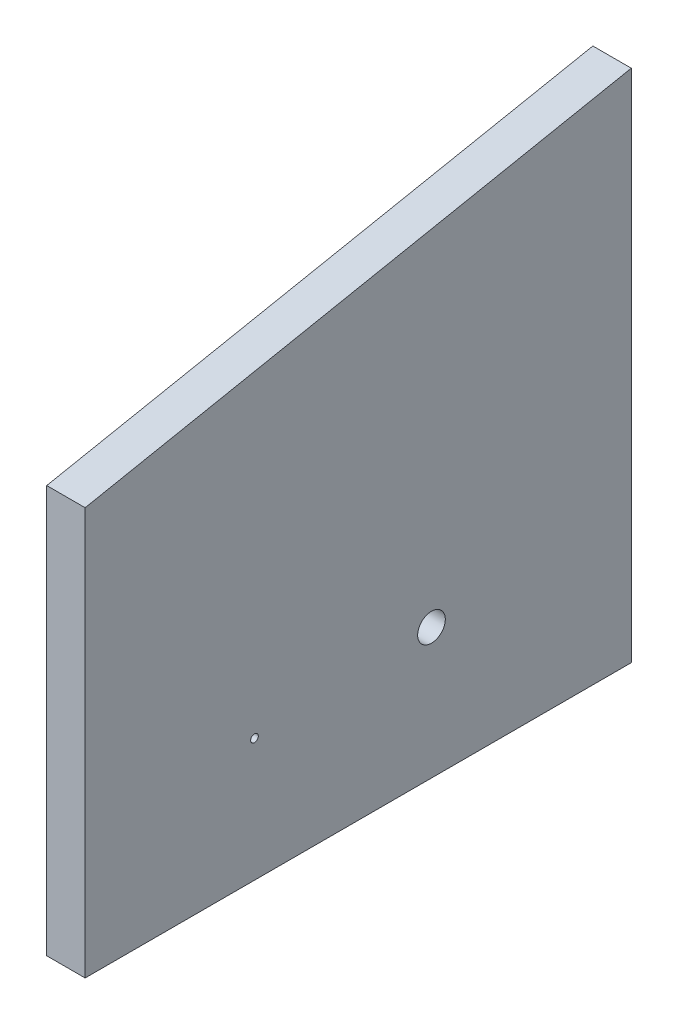
SolidWorks part; units mm, degrees
ref_plane "前视基准面" through (0, 0, 0) normal (0, 0, 1) x (1, 0, 0)
ref_plane "上视基准面" through (0, 0, 0) normal (0, 1, 0) x (1, 0, 0)
ref_plane "右视基准面" through (0, 0, 0) normal (1, 0, 0) x (0, 0, -1)
sketch "Sketch1" plane through (0, 0, 0) normal (0, 1, 0) x (1, 0, 0)
  line L1 (0, 0) -> (50, 0)
  line L2 (0, 0) -> (0, 9.1)
  line L3 (0, 9.1) -> (50, 9.1)
  line L4 (50, 0) -> (50, 9.1)
  dimension "D1" = 50
  dimension "D2" = 9.1
extrude "Boss-Extrude1" add sketch "Sketch1" along normal blind 2
sketch "Sketch2" plane through (0, 2, 0) normal (0, 1, 0) x (1, 0, 0)
  line L0 (50, 9.1) -> (0, 9.1) construction
  line L1 (12.5, 9.1) -> (37.5, 9.1)
  line L2 (12.5, 9.1) -> (12.5, 2.5)
  line L3 (12.5, 2.5) -> (37.5, 2.5)
  line L4 (37.5, 9.1) -> (37.5, 2.5)
  line L5 (0, 9.1) -> (0, 0) construction
  line L6 (50, 0) -> (50, 9.1) construction
  point P8 (50, 4.55)
  dimension "D1" = 6.6
  dimension "D2" = 12.5
  dimension "D3" = 12.5
extrude "Cut-Extrude1" cut sketch "Sketch2" against normal blind 2
sketch "Sketch3" plane through (0, 2, 0) normal (0, 1, 0) x (1, 0, 0)
  line L0 (12.5, 9.1) -> (0, 9.1) construction
  line L1 (50, 9.1) -> (37.5, 9.1) construction
  line L3 (37.5, 2.5) -> (37.5, 9.1) construction
  line L5 (0, 9.1) -> (0, 0) construction
  circle A0 centre (6.25, 5.8) radius 1.8
  circle A1 centre (43.75, 5.8) radius 1.8
  dimension "D1" = 3.6
  dimension "D2" = 3.6
  dimension "D4" = 3.3
  dimension "D3" = 3.3
  dimension "D5" = 6.25
  dimension "D6" = 6.25
extrude "Cut-Extrude2" cut sketch "Sketch3" against normal blind 2
sketch "Sketch4" plane through (0, 2, 0) normal (0, 1, 0) x (1, 0, 0)
  line L0 (0, 0) -> (50, 0) construction
  line L1 (-8.2, 0) -> (58.2, 0)
  line L2 (-8.2, 0) -> (-8.2, -130)
  line L3 (-8.2, -130) -> (58.2, -130)
  line L4 (58.2, 0) -> (58.2, -130)
  line L5 (12.5, 2.5) -> (37.5, 2.5) construction
  point P6 (25, 2.5)
  dimension "D1" = 130
  dimension "D2" = 0
  dimension "D3" = 33.2
  dimension "D4" = 66.4
extrude "Boss-Extrude2" add sketch "Sketch4" against normal blind 2
sketch "Sketch5" plane through (0, 0, 130) normal (0, 0, 1) x (1, 0, 0)
  line L1 (-8.2, 2) -> (58.2, 2)
  line L2 (-8.2, 2) -> (-8.2, 0)
  line L3 (-8.2, 0) -> (58.2, 0)
  line L4 (58.2, 2) -> (58.2, 0)
extrude "Boss-Extrude3" add sketch "Sketch5" along normal blind 2.5
sketch "Sketch6" plane through (0, 2, 0) normal (0, 1, 0) x (1, 0, 0)
  line L1 (-8.2, -132.5) -> (-16.8, -132.5)
  line L2 (-8.2, -132.5) -> (-8.2, -70)
  line L3 (-8.2, -70) -> (-16.8, -70)
  line L4 (-16.8, -132.5) -> (-16.8, -70)
  line L5 (58.2, -132.5) -> (66.8, -132.5)
  line L6 (58.2, -132.5) -> (58.2, -70)
  line L7 (58.2, -70) -> (66.8, -70)
  line L8 (66.8, -132.5) -> (66.8, -70)
  dimension "D1" = 8.6
  dimension "D2" = 8.6
  dimension "D3" = 62.5
  dimension "D4" = 62.5
extrude "Boss-Extrude4" add sketch "Sketch6" against normal blind 2
sketch "Sketch7" plane through (0, 2, 0) normal (0, 1, 0) x (1, 0, 0)
  line L0 (-13.5, -64.2883) -> (-13.5, -157.5169) construction
  line L1 (63.5, -64.2883) -> (63.5, -152.5529) construction
  line L2 (-16.8, -70) -> (-16.8, -132.5) construction
  line L3 (66.8, -132.5) -> (66.8, -70) construction
  line L4 (-8.2, -70) -> (-16.8, -70) construction
  line L5 (66.8, -132.5) -> (-16.8, -132.5) construction
  line L6 (66.8, -70) -> (58.2, -70) construction
  line L7 (-15, -115) -> (-12, -115)
  line L8 (-15, -115) -> (-15, -120)
  line L9 (-15, -120) -> (-12, -120)
  line L10 (-12, -115) -> (-12, -120)
  line L11 (62, -115) -> (65, -115)
  line L12 (62, -115) -> (62, -120)
  line L13 (62, -120) -> (65, -120)
  line L14 (65, -115) -> (65, -120)
  circle A0 centre (-13.5, -77) radius 1.8
  circle A1 centre (-13.5, -101.25) radius 1.8
  circle A2 centre (-13.5, -125.5) radius 1.8
  circle A3 centre (63.5, -77) radius 1.8
  circle A4 centre (63.5, -101.25) radius 1.8
  circle A5 centre (63.5, -125.5) radius 1.8
  dimension "D3" = 3.6
  dimension "D4" = 3.6
  dimension "D6" = 3.6
  dimension "D12" = 3.6
  dimension "D13" = 3.6
  dimension "D14" = 3.6
  dimension "D1" = 3.3
  dimension "D2" = 3.3
  dimension "D5" = 31.25
  dimension "D7" = 7
  dimension "D8" = 1.5
  dimension "D9" = 3
  dimension "D10" = 5
  dimension "D11" = 12.5
  dimension "D15" = 1.5
  dimension "D16" = 3
  dimension "D17" = 7
  dimension "D18" = 7
extrude "Cut-Extrude3" cut sketch "Sketch7" against normal blind 2
sketch "Sketch8" plane through (0, 2, 0) normal (0, 1, 0) x (1, 0, 0)
  line L0 (25, 2.5) -> (25, -143.8166) construction
  line L1 (12.5, 2.5) -> (37.5, 2.5) construction
  line L3 (12.5, 0) -> (37.5, 0)
  line L4 (12.5, 0) -> (12.5, -45)
  line L5 (12.5, -45) -> (37.5, -45)
  line L6 (37.5, 0) -> (37.5, -45)
  dimension "D1" = 25
  dimension "D2" = 12.5
  dimension "D3" = 45
extrude "Cut-Extrude4" cut sketch "Sketch8" against normal blind 20
sketch "Sketch9" plane through (0, 2, 0) normal (0, 1, 0) x (1, 0, 0)
  line L0 (37.5, -45) -> (37.5, 0) construction
  line L1 (12.5, 0) -> (37.5, 0)
  line L2 (12.5, 0) -> (12.5, -10)
  line L3 (12.5, -10) -> (37.5, -10)
  line L4 (37.5, 0) -> (37.5, -10)
  dimension "D1" = 10
extrude "Boss-Extrude5" add sketch "Sketch9" against normal blind 2
sketch "Sketch10" plane through (0, 2, 0) normal (0, 1, 0) x (1, 0, 0)
  line L0 (-8.2, 0) -> (-8.2, -70) construction
  line L1 (-8.2, -16) -> (-42.9, -16)
  line L2 (-8.2, -16) -> (-8.2, -43.07)
  line L3 (-8.2, -43.07) -> (-42.9, -43.07)
  line L4 (-42.9, -16) -> (-42.9, -43.07)
  line L5 (0, 0) -> (-8.2, 0) construction
  line L6 (58.2, -70) -> (58.2, 0) construction
  line L7 (58.2, -16) -> (92.9, -16)
  line L8 (58.2, -16) -> (58.2, -43.07)
  line L9 (58.2, -43.07) -> (92.9, -43.07)
  line L10 (92.9, -16) -> (92.9, -43.07)
  dimension "D1" = 16
  dimension "D2" = 27.07
  dimension "D3" = 34.7
  dimension "D4" = 34.7
extrude "Boss-Extrude6" add sketch "Sketch10" against normal blind 2
sketch "Sketch11" plane through (0, 2, 0) normal (0, 1, 0) x (1, 0, 0)
  line L0 (-48.2559, -39.82) -> (25.7485, -39.82) construction
  line L1 (-47.1851, -19.25) -> (20.7514, -19.25) construction
  line L2 (-8.2, -16) -> (-42.9, -16) construction
  line L3 (-42.9, -43.07) -> (-8.2, -43.07) construction
  line L4 (-42.9, -16) -> (-42.9, -43.07) construction
  circle A0 centre (-36.9, -19.25) radius 1.8
  circle A1 centre (-36.9, -39.82) radius 1.8
  circle A2 centre (-22.6, -19.25) radius 1.8
  circle A3 centre (-22.6, -39.82) radius 1.8
  dimension "D5" = 3.6
  dimension "D6" = 3.6
  dimension "D7" = 3.6
  dimension "D8" = 3.6
  dimension "D10" = 20.3
  dimension "D1" = 3.25
  dimension "D2" = 3.25
  dimension "D3" = 6
  dimension "D4" = 6
  dimension "D9" = 20.3
extrude "Cut-Extrude5" cut sketch "Sketch11" against normal blind 2
sketch "Sketch12" plane through (0, 2, 0) normal (0, 1, 0) x (1, 0, 0)
  line L0 (39.2942, -19.25) -> (115.8735, -19.25) construction
  line L1 (40.8036, -39.82) -> (109.9769, -39.82) construction
  line L2 (92.9, -43.07) -> (92.9, -16) construction
  circle A0 centre (72.6, -19.25) radius 1.8
  circle A1 centre (86.9, -19.25) radius 1.8
  circle A2 centre (72.6, -39.82) radius 1.8
  circle A3 centre (86.9, -39.82) radius 1.8
  dimension "D1" = 3.6
  dimension "D2" = 3.6
  dimension "D5" = 3.6
  dimension "D6" = 3.6
  dimension "D3" = 6
  dimension "D4" = 20.3
extrude "Cut-Extrude6" cut sketch "Sketch12" against normal blind 2
sketch "Sketch13" plane through (-42.9, 0, 0) normal (-1, 0, 0) x (0, 0, 1)
  line L1 (16, 2) -> (14, 2)
  line L2 (16, 2) -> (16, 0)
  line L3 (16, 0) -> (14, 0)
  line L4 (14, 2) -> (14, 0)
  line L5 (43.07, 2) -> (45.07, 2)
  line L6 (43.07, 2) -> (43.07, 0)
  line L7 (43.07, 0) -> (45.07, 0)
  line L8 (45.07, 2) -> (45.07, 0)
  dimension "D1" = 2
  dimension "D2" = 2
extrude "Boss-Extrude7" add sketch "Sketch13" against normal blind 44
sketch "Sketch14" plane through (92.9, 0, 0) normal (1, 0, 0) x (0, 0, -1)
  line L1 (-16, 2) -> (-14, 2)
  line L2 (-16, 2) -> (-16, 0)
  line L3 (-16, 0) -> (-14, 0)
  line L4 (-14, 2) -> (-14, 0)
  line L5 (-43.07, 0) -> (-45.07, 0)
  line L6 (-43.07, 0) -> (-43.07, 2)
  line L7 (-43.07, 2) -> (-45.07, 2)
  line L8 (-45.07, 0) -> (-45.07, 2)
  dimension "D1" = 2
  dimension "D2" = 2
extrude "Boss-Extrude8" add sketch "Sketch14" against normal blind 46
sketch "Sketch16" plane through (0, 2, 0) normal (0, 1, 0) x (1, 0, 0)
  line L0 (66.8, -132.5) -> (-16.8, -132.5) construction
  line L1 (4, -132.5) -> (46, -132.5)
  line L2 (4, -132.5) -> (4, -175.5)
  line L3 (4, -175.5) -> (46, -175.5)
  line L4 (46, -132.5) -> (46, -175.5)
  line L5 (37.5, -45) -> (12.5, -45) construction
  point P6 (25, -45)
  dimension "D1" = 42
  dimension "D2" = 43
  dimension "D3" = 21
extrude "Boss-Extrude10" add sketch "Sketch16" against normal blind 2
sketch "Sketch18" plane through (0, 2, 0) normal (0, 1, 0) x (1, 0, 0)
  line L0 (4, -175.5) -> (46, -175.5) construction
  line L1 (4, -132.5) -> (4, -175.5) construction
  line L2 (46, -175.5) -> (46, -132.5) construction
  line L3 (4, -132.5) -> (-16.8, -132.5) construction
  line L4 (66.8, -132.5) -> (46, -132.5) construction
  circle A0 centre (8.74, -171.03) radius 1.8
  circle A1 centre (41.26, -171.03) radius 1.8
  circle A2 centre (8.74, -138.5) radius 1.8
  circle A3 centre (41.26, -138.5) radius 1.8
  dimension "D3" = 3.6
  dimension "D6" = 3.6
  dimension "D7" = 3.6
  dimension "D8" = 3.6
  dimension "D1" = 4.47
  dimension "D2" = 4.74
  dimension "D4" = 4.47
  dimension "D5" = 4.74
  dimension "D9" = 6
  dimension "D10" = 6
extrude "Cut-Extrude7" cut sketch "Sketch18" against normal blind 2
sketch "Sketch20" plane through (0, 2, 0) normal (0, 1, 0) x (1, 0, 0)
  line L0 (-2, -132.5) -> (4, -132.5)
  line L1 (4, -132.5) -> (-16.8, -132.5) construction
  line L2 (4, -132.5) -> (4, -138.5)
  line L3 (4, -132.5) -> (4, -175.5) construction
  line L4 (46, -138.5) -> (46, -132.5)
  line L5 (46, -175.5) -> (46, -132.5) construction
  line L6 (46, -132.5) -> (52, -132.5)
  line L7 (66.8, -132.5) -> (46, -132.5) construction
  arc A0 (-2, -132.5) -> (4, -138.5) centre (-2, -138.5) cw
  arc A1 (52, -132.5) -> (46, -138.5) centre (52, -138.5) ccw
  dimension "D1" = 6
  dimension "D2" = 6
  dimension "D3" = 6
extrude "Boss-Extrude12" add sketch "Sketch20" against normal blind 2 contours L0 A0 L2 | A1 L6 L4
sketch "Sketch21" plane through (0, 0, -9.1) normal (0, 0, -1) x (-1, 0, 0)
  line L1 (-50, 2) -> (-52, 2)
  line L2 (-50, 2) -> (-50, 0)
  line L3 (-50, 0) -> (-52, 0)
  line L4 (-52, 2) -> (-52, 0)
  line L5 (-37.5, 2) -> (-35.5, 2)
  line L6 (-37.5, 2) -> (-37.5, 0)
  line L7 (-37.5, 0) -> (-35.5, 0)
  line L8 (-35.5, 2) -> (-35.5, 0)
  line L9 (-12.5, 2) -> (-14.5, 2)
  line L10 (-12.5, 2) -> (-12.5, 0)
  line L11 (-12.5, 0) -> (-14.5, 0)
  line L12 (-14.5, 2) -> (-14.5, 0)
  line L13 (0, 2) -> (2, 2)
  line L14 (0, 2) -> (0, 0)
  line L15 (0, 0) -> (2, 0)
  line L16 (2, 2) -> (2, 0)
  dimension "D1" = 2
  dimension "D2" = 2
  dimension "D3" = 2
  dimension "D4" = 2
extrude "Boss-Extrude13" add sketch "Sketch21" against normal blind 10
sketch "Sketch25" plane through (0, 2, 0) normal (0, 1, 0) x (1, 0, 0)
  line L0 (-11.7, -6.4239) -> (-11.7, -56.5762) construction
  line L1 (-8.2, 0) -> (-8.2, -14) construction
  line L2 (61.7, -6.4239) -> (61.7, -56.5762) construction
  line L3 (58.2, -14) -> (58.2, 0) construction
  line L4 (-8.2, -14) -> (-42.9, -14) construction
  line L5 (-13.2, -20) -> (-10.2, -20)
  line L6 (-13.2, -20) -> (-13.2, -25)
  line L7 (-13.2, -25) -> (-10.2, -25)
  line L8 (-10.2, -20) -> (-10.2, -25)
  line L9 (-8.2, -45.07) -> (-42.9, -45.07) construction
  line L10 (-13.2, -34.07) -> (-10.2, -34.07)
  line L11 (-13.2, -34.07) -> (-13.2, -39.07)
  line L12 (-13.2, -39.07) -> (-10.2, -39.07)
  line L13 (-10.2, -34.07) -> (-10.2, -39.07)
  line L14 (58.2, -14) -> (92.9, -14) construction
  line L15 (60.2, -20) -> (63.2, -20)
  line L16 (60.2, -20) -> (60.2, -25)
  line L17 (60.2, -25) -> (63.2, -25)
  line L18 (63.2, -20) -> (63.2, -25)
  line L19 (60.2, -34.07) -> (63.2, -34.07)
  line L20 (60.2, -34.07) -> (60.2, -39.07)
  line L21 (60.2, -39.07) -> (63.2, -39.07)
  line L22 (63.2, -34.07) -> (63.2, -39.07)
  line L23 (58.2, -45.07) -> (92.9, -45.07) construction
  dimension "D1" = 3.5
  dimension "D2" = 3.5
  dimension "D3" = 3
  dimension "D4" = 1.5
  dimension "D5" = 5
  dimension "D6" = 6
  dimension "D7" = 5
  dimension "D8" = 6
  dimension "D9" = 3
  dimension "D10" = 1.5
  dimension "D11" = 1.5
  dimension "D12" = 3
  dimension "D13" = 1.5
  dimension "D14" = 3
  dimension "D15" = 6
  dimension "D16" = 6
extrude "Cut-Extrude8" cut sketch "Sketch25" against normal blind 10
sketch "Sketch26" plane through (0, 2, 0) normal (0, 1, 0) x (1, 0, 0)
  line L1 (-2, 0) -> (-8.2, 0)
  line L2 (-2, 0) -> (-2, 13)
  line L3 (-2, 13) -> (-8.2, 13)
  line L4 (-8.2, 0) -> (-8.2, 13)
  line L5 (58.2, 0) -> (52, 0)
  line L6 (58.2, 0) -> (58.2, 13)
  line L7 (58.2, 13) -> (52, 13)
  line L8 (52, 0) -> (52, 13)
  line L9 (-2, 13) -> (52, 13)
  line L10 (-2, 13) -> (-2, 9.1)
  line L11 (-2, 9.1) -> (52, 9.1)
  line L12 (52, 13) -> (52, 9.1)
  line L13 (35.5, 2.5) -> (14.5, 2.5)
  line L14 (35.5, 2.5) -> (35.5, 9.1)
  line L15 (35.5, 9.1) -> (14.5, 9.1)
  line L16 (14.5, 2.5) -> (14.5, 9.1)
  dimension "D1" = 13
extrude "Boss-Extrude14" add sketch "Sketch26" against normal blind 2 contours L4 L1 L2 L3 | L2 L11 L8 L9 | L16 L13 L14 L11 | L8 L5 L6 L7
sketch "Sketch27" plane through (0, 2, 0) normal (0, 1, 0) x (1, 0, 0)
  line L0 (-8.2, -14) -> (-42.9, -14) construction
  line L1 (-8.2, 13) -> (-10.2, 13)
  line L2 (-8.2, 13) -> (-8.2, -14)
  line L3 (-8.2, -14) -> (-10.2, -14)
  line L4 (-10.2, 13) -> (-10.2, -14)
  line L5 (-8.2, -45.07) -> (-42.9, -45.07) construction
  line L6 (-10.2, -45.07) -> (-8.2, -45.07)
  line L7 (-10.2, -45.07) -> (-10.2, -70)
  line L8 (-10.2, -70) -> (-8.2, -70)
  line L9 (-8.2, -45.07) -> (-8.2, -70)
  line L10 (58.2, -14) -> (92.9, -14) construction
  line L11 (58.2, 13) -> (60.2, 13)
  line L12 (58.2, 13) -> (58.2, -14)
  line L13 (58.2, -14) -> (60.2, -14)
  line L14 (60.2, 13) -> (60.2, -14)
  line L15 (66.8, -70) -> (58.2, -70) construction
  line L16 (58.2, -45.07) -> (60.2, -45.07)
  line L17 (58.2, -45.07) -> (58.2, -70)
  line L18 (58.2, -70) -> (60.2, -70)
  line L19 (60.2, -45.07) -> (60.2, -70)
extrude "Boss-Extrude15" add sketch "Sketch27" against normal blind 2
sketch "Sketch29" plane through (0, 2, 0) normal (0, 1, 0) x (1, 0, 0)
  line L1 (-10.2, -14) -> (-20.2, -14)
  line L2 (-10.2, -14) -> (-10.2, -4)
  line L3 (-10.2, -4) -> (-20.2, -4)
  line L4 (-20.2, -14) -> (-20.2, -4)
  line L5 (-10.2, -45.07) -> (-20.2, -45.07)
  line L6 (-10.2, -45.07) -> (-10.2, -55.07)
  line L7 (-10.2, -55.07) -> (-20.2, -55.07)
  line L8 (-20.2, -45.07) -> (-20.2, -55.07)
  line L9 (60.2, -14) -> (70.2, -14)
  line L10 (60.2, -14) -> (60.2, -4)
  line L11 (60.2, -4) -> (70.2, -4)
  line L12 (70.2, -14) -> (70.2, -4)
  line L13 (60.2, -45.07) -> (70.2, -45.07)
  line L14 (60.2, -45.07) -> (60.2, -55.07)
  line L15 (60.2, -55.07) -> (70.2, -55.07)
  line L16 (70.2, -45.07) -> (70.2, -55.07)
  dimension "D1" = 10
  dimension "D2" = 10
  dimension "D3" = 10
  dimension "D4" = 10
  dimension "D5" = 10
  dimension "D6" = 10
  dimension "D7" = 10
extrude "Boss-Extrude19" add sketch "Sketch29" against normal blind 2
sketch "Sketch41" plane through (0, 2, 0) normal (0, 1, 0) x (1, 0, 0)
  circle A0 centre (-15.2, -9) radius 1.8
  circle A1 centre (-15.2, -50.07) radius 1.8
  circle A2 centre (65.2, -9) radius 1.8
  circle A3 centre (65.2, -50.07) radius 1.8
  dimension "D1" = 3.6
  dimension "D2" = 3.6
  dimension "D3" = 3.6
  dimension "D4" = 3.6
extrude "Cut-Extrude15" cut sketch "Sketch41" against normal blind 2
sketch "Sketch42" plane through (0, 2, 0) normal (0, 1, 0) x (1, 0, 0)
  line L0 (60.2, -70) -> (60.2, -55.07) construction
  line L1 (-10.2, -70) -> (-16.8, -70) construction
  line L2 (-16.8, -70) -> (-10.2, -70)
  line L3 (-10.2, -70) -> (-10.2, -63.4)
  line L4 (60.2, -63.4) -> (60.2, -70)
  line L5 (60.2, -70) -> (66.8, -70)
  arc A0 (-16.8, -70) -> (-10.2, -63.4) centre (-16.8, -63.4) ccw
  arc A1 (66.8, -70) -> (60.2, -63.4) centre (66.8, -63.4) cw
  dimension "D1" = 6.6
extrude "Boss-Extrude26" add sketch "Sketch42" against normal blind 2
sketch "Sketch43" plane through (0, 0, -13) normal (0, 0, -1) x (-1, 0, 0)
  line L1 (10.2, 2) -> (-60.2, 2)
  line L2 (10.2, 2) -> (10.2, 0)
  line L3 (10.2, 0) -> (-60.2, 0)
  line L4 (-60.2, 2) -> (-60.2, 0)
extrude "Boss-Extrude27" add sketch "Sketch43" along normal blind 11
sketch "Sketch44" plane through (0, 2, 0) normal (0, 1, 0) x (1, 0, 0)
  line L0 (-10.2, -55.07) -> (-10.2, -63.4) construction
  line L1 (-20.2, -55.07) -> (-10.2, -55.07)
  line L2 (-20.2, -55.07) -> (-20.2, -60.07)
  line L3 (-20.2, -60.07) -> (-10.2, -60.07)
  line L4 (-10.2, -55.07) -> (-10.2, -60.07)
  line L5 (60.2, -63.4) -> (60.2, -55.07) construction
  line L6 (70.2, -55.07) -> (60.2, -55.07)
  line L7 (70.2, -55.07) -> (70.2, -60.07)
  line L8 (70.2, -60.07) -> (60.2, -60.07)
  line L9 (60.2, -55.07) -> (60.2, -60.07)
  dimension "D1" = 5
extrude "Boss-Extrude28" add sketch "Sketch44" against normal blind 2
sketch "Sketch45" plane through (0, 2, 0) normal (0, 1, 0) x (1, 0, 0)
  circle A0 centre (-15.2, -50.07) radius 1.8
  circle A1 centre (65.2, -50.07) radius 1.8
extrude "Boss-Extrude29" add sketch "Sketch45" against normal blind 2
sketch "Sketch46" plane through (0, 2, 0) normal (0, 1, 0) x (1, 0, 0)
  line L0 (-20.2, -60.07) -> (-10.2, -60.07) construction
  line L1 (60.2, -60.07) -> (70.2, -60.07) construction
  line L2 (-20.2, -45.07) -> (-20.2, -60.07) construction
  line L3 (70.2, -60.07) -> (70.2, -45.07) construction
  circle A0 centre (-15.2, -55.07) radius 1.8
  circle A1 centre (65.2, -55.07) radius 1.8
  dimension "D2" = 3.6
  dimension "D3" = 3.6
  dimension "D1" = 5
  dimension "D4" = 5
  dimension "D5" = 5
  dimension "D6" = 5
extrude "Cut-Extrude16" cut sketch "Sketch46" against normal blind 2
sketch "Sketch47" plane through (0, 2, 0) normal (0, 1, 0) x (1, 0, 0)
  line L0 (-10.2, 24) -> (-10.2, -4) construction
  line L1 (-20.2, -4) -> (-10.2, -4)
  line L2 (-20.2, -4) -> (-20.2, -3)
  line L3 (-20.2, -3) -> (-10.2, -3)
  line L4 (-10.2, -4) -> (-10.2, -3)
  line L5 (-10.2, -60.07) -> (-10.2, -63.4) construction
  line L6 (-20.2, -60.07) -> (-10.2, -60.07)
  line L7 (-20.2, -60.07) -> (-20.2, -61.07)
  line L8 (-20.2, -61.07) -> (-10.2, -61.07)
  line L9 (-10.2, -60.07) -> (-10.2, -61.07)
  line L10 (60.2, -63.4) -> (60.2, -60.07) construction
  line L11 (60.2, -4) -> (70.2, -4)
  line L12 (60.2, -4) -> (60.2, -3)
  line L13 (60.2, -3) -> (70.2, -3)
  line L14 (70.2, -4) -> (70.2, -3)
  line L15 (70.2, -60.07) -> (60.2, -60.07)
  line L16 (70.2, -60.07) -> (70.2, -61.07)
  line L17 (70.2, -61.07) -> (60.2, -61.07)
  line L18 (60.2, -60.07) -> (60.2, -61.07)
  dimension "D1" = 1
  dimension "D2" = 1
extrude "Boss-Extrude30" add sketch "Sketch47" against normal blind 2
sketch "Sketch48" plane through (0, 2, 0) normal (0, 1, 0) x (1, 0, 0)
  line L1 (-42.9, -14) -> (-10.2, -14)
  line L2 (-42.9, -14) -> (-42.9, -45.07)
  line L3 (-42.9, -45.07) -> (-10.2, -45.07)
  line L4 (-10.2, -14) -> (-10.2, -45.07)
  line L5 (92.9, -14) -> (60.2, -14)
  line L6 (92.9, -14) -> (92.9, -45.07)
  line L7 (92.9, -45.07) -> (60.2, -45.07)
  line L8 (60.2, -14) -> (60.2, -45.07)
  line L9 (-20.2, -61.07) -> (81.55, -61.07)
  line L10 (-20.2, -61.07) -> (-20.2, -181.5574)
  line L11 (-20.2, -181.5574) -> (81.55, -181.5574)
  line L12 (81.55, -61.07) -> (81.55, -181.5574)
extrude "Cut-Extrude17" cut sketch "Sketch48" against normal blind 20
sketch "Sketch50" plane through (0, 2, 0) normal (0, 1, 0) x (1, 0, 0)
  line L0 (-10.2, 24) -> (-10.2, -3) construction
  line L1 (-8.2, 22) -> (58.2, 22)
  line L2 (-8.2, 22) -> (-8.2, -59.07)
  line L3 (-8.2, -59.07) -> (58.2, -59.07)
  line L4 (58.2, 22) -> (58.2, -59.07)
  line L5 (-10.2, 24) -> (60.2, 24) construction
  line L6 (-20.2, -61.07) -> (70.2, -61.07) construction
  line L7 (60.2, -3) -> (60.2, 24) construction
  dimension "D1" = 2
  dimension "D2" = 2
  dimension "D3" = 2
  dimension "D4" = 2
extrude "Cut-Extrude19" cut sketch "Sketch50" against normal blind 20
sketch "Sketch51" plane through (0, 2, 0) normal (0, 1, 0) x (1, 0, 0)
  line L0 (-20.2, -61.07) -> (70.2, -61.07) construction
  line L1 (-10.2, 24) -> (60.2, 24)
  line L2 (-10.2, 24) -> (-10.2, -61.07)
  line L3 (-10.2, -61.07) -> (60.2, -61.07)
  line L4 (60.2, 24) -> (60.2, -61.07)
  line L6 (58.2, -59.07) -> (-8.2, -59.07)
  line L7 (58.2, -59.07) -> (58.2, 22)
  line L8 (58.2, 22) -> (-8.2, 22)
  line L9 (-8.2, -59.07) -> (-8.2, 22)
extrude "Boss-Extrude31" add sketch "Sketch51" along normal blind 20
sketch "Sketch52" plane through (0, 2, 0) normal (0, 1, 0) x (1, 0, 0)
  line L0 (-10.2, 24) -> (-10.2, -61.07) construction
  line L1 (-20.2, -14) -> (-10.2, -14)
  line L2 (-20.2, -14) -> (-20.2, -15)
  line L3 (-20.2, -15) -> (-10.2, -15)
  line L4 (-10.2, -14) -> (-10.2, -15)
  line L5 (60.2, -61.07) -> (60.2, 24) construction
  line L6 (70.2, -14) -> (60.2, -14)
  line L7 (70.2, -14) -> (70.2, -15)
  line L8 (70.2, -15) -> (60.2, -15)
  line L9 (60.2, -14) -> (60.2, -15)
  dimension "D1" = 1
extrude "Boss-Extrude32" add sketch "Sketch52" against normal blind 2
sketch "Sketch53" plane through (0, 2, 0) normal (0, 1, 0) x (1, 0, 0)
  line L0 (-10.2, 24) -> (-10.2, -61.07) construction
  line L1 (-20.2, -45.07) -> (-10.2, -45.07)
  line L2 (-20.2, -45.07) -> (-20.2, -49.07)
  line L3 (-20.2, -49.07) -> (-10.2, -49.07)
  line L4 (-10.2, -45.07) -> (-10.2, -49.07)
  line L5 (60.2, -61.07) -> (60.2, 24) construction
  line L6 (70.2, -45.07) -> (60.2, -45.07)
  line L7 (70.2, -45.07) -> (70.2, -49.07)
  line L8 (70.2, -49.07) -> (60.2, -49.07)
  line L9 (60.2, -45.07) -> (60.2, -49.07)
  dimension "D1" = 4
  dimension "D2" = 4
extrude "Cut-Extrude20" cut sketch "Sketch53" against normal blind 2
sketch "Sketch54" plane through (0, 2, 0) normal (0, 1, 0) x (1, 0, 0)
  line L1 (-20.2, -3) -> (-10.2, -3)
  line L2 (-20.2, -3) -> (-20.2, -15)
  line L3 (-20.2, -15) -> (-10.2, -15)
  line L4 (-10.2, -3) -> (-10.2, -15)
  line L5 (-20.2, -49.07) -> (-10.2, -49.07)
  line L6 (-20.2, -49.07) -> (-20.2, -61.07)
  line L7 (-20.2, -61.07) -> (-10.2, -61.07)
  line L8 (-10.2, -49.07) -> (-10.2, -61.07)
  line L9 (60.2, -3) -> (70.2, -3)
  line L10 (60.2, -3) -> (60.2, -15)
  line L11 (60.2, -15) -> (70.2, -15)
  line L12 (70.2, -3) -> (70.2, -15)
  line L13 (60.2, -49.07) -> (70.2, -49.07)
  line L14 (60.2, -49.07) -> (60.2, -61.07)
  line L15 (60.2, -61.07) -> (70.2, -61.07)
  line L16 (70.2, -49.07) -> (70.2, -61.07)
  circle A0 centre (-15.2, -9) radius 1.8
  circle A1 centre (-15.2, -55.07) radius 1.8
  circle A2 centre (65.2, -9) radius 1.8
  circle A3 centre (65.2, -55.07) radius 1.8
extrude "Boss-Extrude33" add sketch "Sketch54" along normal blind 1
sketch "Sketch55" plane through (0, 0, 3) normal (0, 0, -1) x (-1, 0, 0)
  line L0 (20.2, 3) -> (10.2, 22)
  line L1 (10.2, 22) -> (10.2, 3)
  line L2 (10.2, 3) -> (20.2, 3)
  line L3 (-70.2, 3) -> (-60.2, 3)
  line L4 (-60.2, 3) -> (-60.2, 22)
  line L5 (-60.2, 22) -> (-70.2, 3)
sketch "Sketch56" plane through (0, 0, 15) normal (0, 0, 1) x (1, 0, 0)
  line L0 (-20.2, 3) -> (-10.2, 3)
  line L1 (-10.2, 3) -> (-10.2, 22)
  line L2 (-10.2, 22) -> (-20.2, 3)
  line L3 (70.2, 3) -> (60.2, 3)
  line L4 (60.2, 3) -> (60.2, 22)
  line L5 (60.2, 22) -> (70.2, 3)
sketch "Sketch57" plane through (0, 0, 49.07) normal (0, 0, -1) x (-1, 0, 0)
  line L0 (20.2, 3) -> (10.2, 3)
  line L1 (10.2, 22) -> (20.2, 3)
  line L2 (-70.2, 3) -> (-60.2, 3)
  line L3 (-60.2, 3) -> (-60.2, 22)
  line L4 (-60.2, 22) -> (-70.2, 3)
  line L5 (10.2, 3) -> (10.2, 22)
sketch "Sketch59" plane through (0, 0, -22) normal (0, 0, 1) x (1, 0, 0)
  line L0 (-8.2, 11) -> (58.2, 11) construction
  line L1 (-8.2, 0) -> (-8.2, 22) construction
  line L2 (58.2, 0) -> (58.2, 22) construction
  circle A0 centre (-3.2, 11) radius 1.8
  circle A1 centre (53.2, 11) radius 1.8
  circle A2 centre (25, 11) radius 1.8
  dimension "D1" = 3.6
  dimension "D2" = 3.6
  dimension "D5" = 3.6
  dimension "D3" = 5
  dimension "D4" = 5
extrude "Cut-Extrude23" cut sketch "Sketch59" against normal blind 16 and the other way blind 96
sketch "Sketch62" plane through (0, 0, 61.07) normal (0, 0, 1) x (1, 0, 0)
  line L1 (-8.5777, 16.369) -> (58.4073, 16.369)
  line L2 (-8.5777, 16.369) -> (-8.5777, 5.1196)
  line L3 (-8.5777, 5.1196) -> (58.4073, 5.1196)
  line L4 (58.4073, 16.369) -> (58.4073, 5.1196)
extrude "Boss-Extrude38" add sketch "Sketch62" against normal blind 1
sketch "Sketch65" plane through (0, 0, 59.07) normal (0, 0, -1) x (-1, 0, 0)
  line L0 (8.2, 11) -> (-58.2, 11) construction
  line L1 (8.2, 0) -> (8.2, 22) construction
  line L2 (-58.2, 0) -> (-58.2, 22) construction
  circle A0 centre (-13.8, 11) radius 1.8
  circle A1 centre (-36.2, 11) radius 1.8
  dimension "D2" = 3.6
  dimension "D4" = 3.6
  dimension "D1" = 22
  dimension "D3" = 22
extrude "Cut-Extrude27" cut sketch "Sketch65" against normal blind 3
sketch "Sketch66" plane through (-10.2, 0, 0) normal (-1, 0, 0) x (0, 0, 1)
  line L0 (-24, 22) -> (61.07, 22) construction
  circle A0 centre (32.035, 16) radius 1
  dimension "D1" = 6
  dimension "D2" = 2
extrude "Cut-Extrude28" cut sketch "Sketch66" against normal blind 87
extrude "Boss-Extrude41" add sketch "Sketch55" against normal blind 2
extrude "Boss-Extrude42" add sketch "Sketch56" against normal blind 2
extrude "Boss-Extrude43" add sketch "Sketch57" against normal blind 2
sketch "Sketch68" plane through (0, 0, 59.07) normal (0, 0, -1) x (-1, 0, 0)
  line L1 (-0.8965, 6.2744) -> (5.8953, 6.2744)
  line L2 (-0.8965, 6.2744) -> (-0.8965, 14.4185)
  line L3 (-0.8965, 14.4185) -> (5.8953, 14.4185)
  line L4 (5.8953, 6.2744) -> (5.8953, 14.4185)
  line L5 (-21.8815, 6.2744) -> (-27.3672, 6.2744)
  line L6 (-21.8815, 6.2744) -> (-21.8815, 14.4185)
  line L7 (-21.8815, 14.4185) -> (-27.3672, 14.4185)
  line L8 (-27.3672, 6.2744) -> (-27.3672, 14.4185)
  line L9 (-48.3497, 6.2744) -> (-56.1137, 6.2744)
  line L10 (-48.3497, 6.2744) -> (-48.3497, 17.9033)
  line L11 (-48.3497, 17.9033) -> (-56.1137, 17.9033)
  line L12 (-56.1137, 6.2744) -> (-56.1137, 17.9033)
extrude "Boss-Extrude44" add sketch "Sketch68" against normal blind 2
sketch "Sketch69" plane through (0, 0, 61.07) normal (0, 0, 1) x (1, 0, 0)
  line L0 (-20.2, 3) -> (-10.2, 3)
  line L1 (-10.2, 3) -> (-10.2, 22)
  line L2 (-10.2, 22) -> (-20.2, 3)
  line L3 (60.2, 3) -> (70.2, 3)
  line L4 (70.2, 3) -> (60.2, 22)
  line L5 (60.2, 22) -> (60.2, 3)
extrude "Boss-Extrude45" add sketch "Sketch69" against normal blind 2
sketch "Sketch70" plane through (-10.2, 0, 0) normal (-1, 0, 0) x (0, 0, 1)
  line L0 (5, 22) -> (13, 22) construction
  circle A0 centre (9, 17) radius 1.8
  circle A1 centre (55.07, 17) radius 1.8
  dimension "D1" = 3.6
  dimension "D3" = 3.6
  dimension "D2" = 5
extrude "Cut-Extrude29" cut sketch "Sketch70" against normal blind 83
sketch "Sketch71" plane through (-8.2, 0, 0) normal (1, 0, 0) x (0, 0, -1)
  line L1 (22, 22) -> (27.8761, 22)
  line L2 (22, 22) -> (22, -17.4815)
  line L3 (22, -17.4815) -> (27.8761, -17.4815)
  line L4 (27.8761, 22) -> (27.8761, -17.4815)
extrude "Cut-Extrude30" cut sketch "Sketch71" against normal blind 16 and the other way blind 75
sketch "Sketch72" plane through (0, 22, 0) normal (0, 1, 0) x (1, 0, 0)
  line L1 (-1.2414, 25.9888) -> (78.3695, 25.9888)
  line L2 (-1.2414, 25.9888) -> (-1.2414, -66.4903)
  line L3 (-1.2414, -66.4903) -> (78.3695, -66.4903)
  line L4 (78.3695, 25.9888) -> (78.3695, -66.4903)
extrude "Cut-Extrude31" cut sketch "Sketch72" against normal blind 40
sketch "Sketch73" plane through (-8.2, 0, 0) normal (1, 0, 0) x (0, 0, -1)
  line L1 (-59.07, 22) -> (-66.1954, 22)
  line L2 (-59.07, 22) -> (-59.07, -28.8749)
  line L3 (-59.07, -28.8749) -> (-66.1954, -28.8749)
  line L4 (-66.1954, 22) -> (-66.1954, -28.8749)
extrude "Cut-Extrude32" cut sketch "Sketch73" against normal blind 22 and the other way blind 43
sketch "Sketch74" plane through (0, 0, 3) normal (0, 0, -1) x (-1, 0, 0)
  line L1 (10.2, 0) -> (62.4549, 0)
  line L2 (10.2, 0) -> (10.2, 40.3348)
  line L3 (10.2, 40.3348) -> (62.4549, 40.3348)
  line L4 (62.4549, 0) -> (62.4549, 40.3348)
extrude "Cut-Extrude33" cut sketch "Sketch74" against normal blind 68
sketch "Sketch75" plane through (-10.2, 0, 0) normal (-1, 0, 0) x (0, 0, 1)
  line L1 (-22, 0) -> (59.07, 0)
  line L2 (-22, 0) -> (-22, 22)
  line L3 (-22, 22) -> (59.07, 22)
  line L4 (59.07, 0) -> (59.07, 22)
  circle A0 centre (9, 17) radius 1.8
  circle A1 centre (32.035, 16) radius 1
  circle A2 centre (55.07, 17) radius 1.8
extrude "Boss-Extrude46" add sketch "Sketch75" along normal blind 3
sketch "Sketch76" plane through (-13.2, 0, 0) normal (-1, 0, 0) x (0, 0, 1)
  circle A0 centre (55.07, 17) radius 1.8
  circle A1 centre (32.035, 16) radius 1
  circle A2 centre (32.035, 16) radius 0.5
  dimension "D1" = 1
extrude "Boss-Extrude47" add sketch "Sketch76" against normal blind 5
sketch "Sketch77" plane through (0, 0, 59.07) normal (0, 0, 1) x (1, 0, 0)
  line L1 (-13.2, 0) -> (-8.2, 0)
  line L2 (-13.2, 0) -> (-13.2, 22)
  line L3 (-13.2, 22) -> (-8.2, 22)
  line L4 (-8.2, 0) -> (-8.2, 22)
extrude "Cut-Extrude34" cut sketch "Sketch77" against normal blind 5
sketch "Sketch78" plane through (0, 0, -22) normal (0, 0, -1) x (-1, 0, 0)
  line L1 (8.2, 0) -> (13.2, 0)
  line L2 (8.2, 0) -> (8.2, 22)
  line L3 (8.2, 22) -> (13.2, 22)
  line L4 (13.2, 0) -> (13.2, 22)
extrude "Cut-Extrude35" cut sketch "Sketch78" against normal blind 5
sketch "Sketch79" plane through (-13.2, 0, 0) normal (-1, 0, 0) x (0, 0, 1)
  line L0 (-17, 22) -> (-17, 67)
  line L1 (-17, 67) -> (54.07, 53)
  line L2 (54.07, 53) -> (54.07, 22)
  line L3 (54.07, 22) -> (-17, 22)
  dimension "D1" = 31
  dimension "D2" = 45
extrude "Boss-Extrude49" add sketch "Sketch79" against normal blind 5
